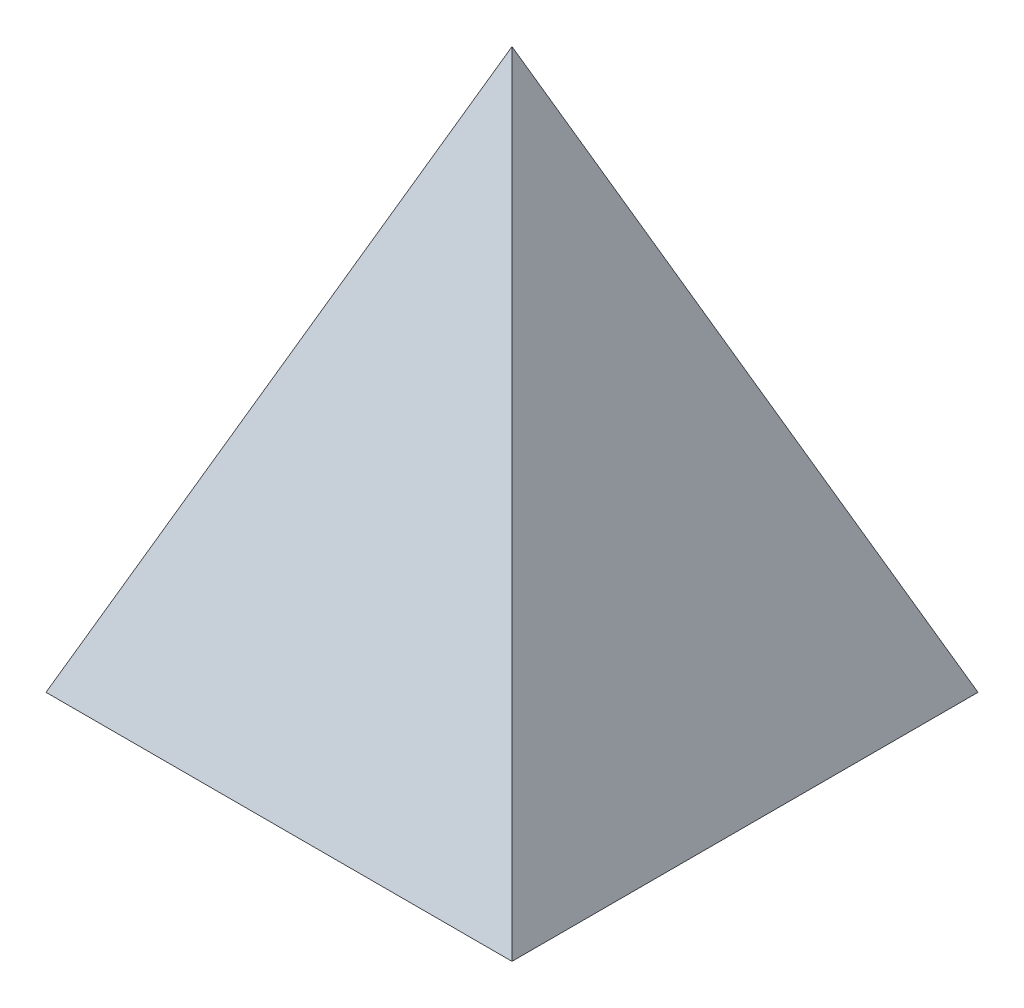
SolidWorks part; units mm, degrees
ref_plane "Alzado" through (0, 0, 0) normal (0, 0, 1) x (1, 0, 0)
ref_plane "Planta" through (0, 0, 0) normal (0, 1, 0) x (1, 0, 0)
ref_plane "Vista lateral" through (0, 0, 0) normal (1, 0, 0) x (0, 0, -1)
sketch "Croquis_triangulo_frontal" plane through (0, 0, 0) normal (0, 0, 1) x (1, 0, 0)
  line L0 (-50, 0) -> (50, 0)
  line L1 (50, 0) -> (0, 120)
  line L2 (0, 120) -> (-50, 0)
  dimension "D1" = 50
  dimension "D2" = 120
extrude "Cuna" add sketch "Croquis_triangulo_frontal" along normal mid plane 100
sketch "Croquis_recorte_lateral" plane through (0, 0, 0) normal (1, 0, 0) x (0, 0, -1)
  line L0 (-60, 0) -> (-50, 0)
  line L1 (-50, 0) -> (0, 120)
  line L2 (0, 120) -> (50, 0)
  line L3 (50, 0) -> (60, 0)
  line L4 (60, 0) -> (60, 130)
  line L5 (60, 130) -> (-60, 130)
  line L6 (-60, 130) -> (-60, 0)
  dimension "D1" = 10
  dimension "D2" = 60
  dimension "D3" = 120
extrude "Recorte_caras_piramide" cut sketch "Croquis_recorte_lateral" against normal through all and the other way through all
sketch "Croquis_agujeros_montaje" plane through (0, 0, 0) normal (0, 1, 0) x (1, 0, 0)
  circle A0 centre (0, 0) radius 4
  dimension "D1" = 8
extrude "Agujero_inserto_M6" cut sketch "Croquis_agujeros_montaje" along normal blind 14
